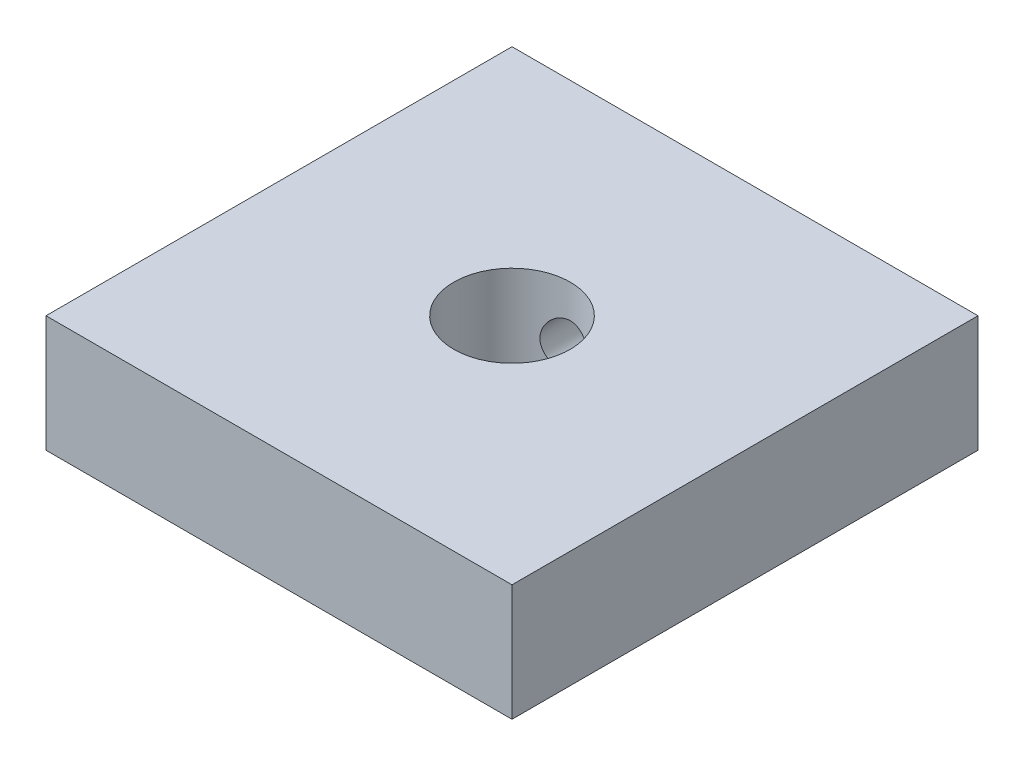
SolidWorks part; units mm, degrees
ref_plane "Front Plane" through (0, 0, 0) normal (0, 0, 1) x (1, 0, 0)
ref_plane "Top Plane" through (0, 0, 0) normal (0, 1, 0) x (1, 0, 0)
ref_plane "Right Plane" through (0, 0, 0) normal (1, 0, 0) x (0, 0, -1)
sketch "Sketch1" plane through (0, 0, 0) normal (0, 1, 0) x (1, 0, 0)
  line L1 (-12.7, -12.7) -> (12.7, -12.7)
  line L2 (-12.7, -12.7) -> (-12.7, 12.7)
  line L3 (-12.7, 12.7) -> (12.7, 12.7)
  line L4 (12.7, -12.7) -> (12.7, 12.7)
  line L5 (-12.7, -12.7) -> (12.7, 12.7) construction
  line L6 (-12.7, 12.7) -> (12.7, -12.7) construction
  point P0 (0, 0)
  dimension "D1" = 25.4
  dimension "D2" = 25.4
extrude "Boss-Extrude1" add sketch "Sketch1" along normal blind 6.35
sketch "Sketch2" plane through (0, 6.35, 0) normal (0, 1, 0) x (1, 0, 0)
  circle A0 centre (0, 0) radius 3.175
  dimension "D1" = 6.35
extrude "Cut-Extrude1" cut sketch "Sketch2" against normal through all
hole_wizard "#6-32 Tapped Hole1" positions "Sketch3" profile "Sketch4" tap size "#6-32" standard "ANSI Inch"
sketch "Sketch3" plane through (0, 0, -12.7) normal (0, 0, -1) x (-1, 0, 0)
  line L0 (0, 6.35) -> (0, 0) construction
  line L1 (-12.7, 6.35) -> (12.7, 6.35) construction
  line L2 (-12.7, 0) -> (12.7, 0) construction
  point P9 (0, 3.175)
sketch "Sketch4" plane through (0, 3.175, -12.7) normal (1, 0, 0) x (0, 1, 0)
  line L0 (0, 0) -> (0, 9.525)
  line L1 (0, 9.525) -> (1.3525, 9.525)
  line L2 (1.3525, 9.525) -> (1.3525, 0)
  line L5 (1.3525, 0) -> (0, 0)
  line L11 (0, -6.35) -> (0, 107.95) construction
  dimension "Thru Tap Drill Dia." = 2.7051
  dimension "Thru Tap Drill Depth" = 9.525
